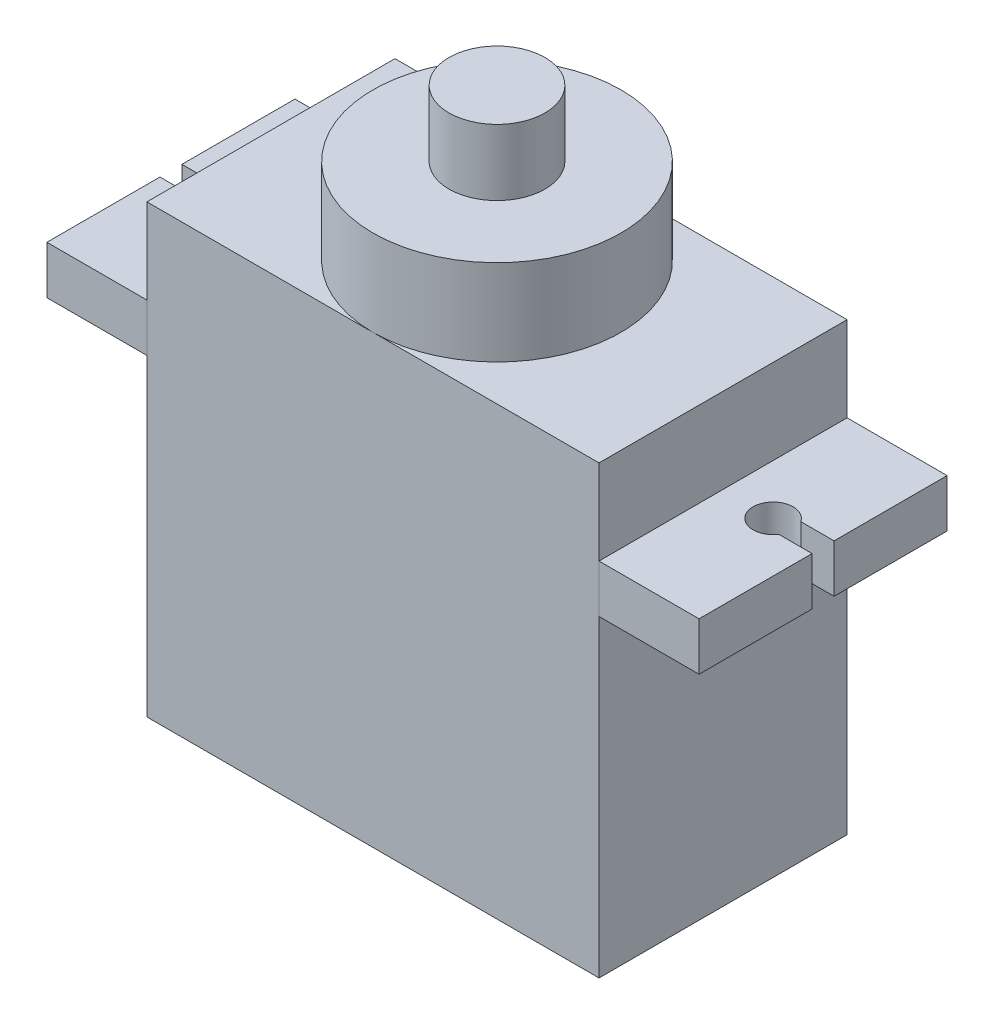
SolidWorks part; units mm, degrees
ref_plane "前视基准面" through (0, 0, 0) normal (0, 0, 1) x (1, 0, 0)
ref_plane "上视基准面" through (0, 0, 0) normal (0, 1, 0) x (1, 0, 0)
ref_plane "右视基准面" through (0, 0, 0) normal (1, 0, 0) x (0, 0, -1)
sketch "草图1" plane through (0, 0, 0) normal (0, 1, 0) x (1, 0, 0)
  line L1 (-11.3, 6.2) -> (11.3, 6.2)
  line L2 (-11.3, 6.2) -> (-11.3, -6.2)
  line L3 (-11.3, -6.2) -> (11.3, -6.2)
  line L4 (11.3, 6.2) -> (11.3, -6.2)
  line L5 (0, -6.2) -> (0, 6.2) construction
  line L6 (-11.3, 0) -> (11.3, 0) construction
  point P0 (0, 0)
  dimension "D1" = 22.6
  dimension "D2" = 12.4
extrude "凸台-拉伸1" add sketch "草图1" along normal blind 22.3
sketch "草图2" plane through (0, 0, 6.2) normal (0, 0, 1) x (1, 0, 0)
  line L0 (11.3, 22.3) -> (11.3, 0) construction
  line L1 (11.3, 18.05) -> (16.3, 18.05)
  line L2 (11.3, 18.05) -> (11.3, 15.65)
  line L3 (11.3, 15.65) -> (16.3, 15.65)
  line L4 (16.3, 18.05) -> (16.3, 15.65)
  line L5 (-11.3, 22.3) -> (11.3, 22.3) construction
  line L6 (0, 0) -> (0, 13.1092) construction
  line L7 (-11.3, 15.65) -> (-16.3, 15.65)
  line L8 (-16.3, 18.05) -> (-16.3, 15.65)
  line L9 (-11.3, 18.05) -> (-16.3, 18.05)
  line L10 (-11.3, 18.05) -> (-11.3, 15.65)
  dimension "D1" = 4.25
  dimension "D2" = 2.4
  dimension "D3" = 5
extrude "凸台-拉伸2" add sketch "草图2" against normal through all separate body
sketch "草图3" plane through (0, 18.05, 0) normal (0, 1, 0) x (1, 0, 0)
  line L0 (14.6352, 0.55) -> (16.3, 0.55)
  line L1 (16.3, 6.2) -> (16.3, -6.2) construction
  line L2 (16.3, 0.55) -> (16.3, -0.55)
  line L3 (16.3, -0.55) -> (14.6352, -0.55)
  line L4 (0, 0) -> (13.8, 0) construction
  line L5 (0, 0) -> (0, 7.8737) construction
  line L12 (-14.6352, -0.55) -> (-16.3, -0.55)
  line L13 (-16.3, 0.55) -> (-14.6352, 0.55)
  line L19 (-16.3, 0.55) -> (-16.3, -0.55)
  arc A0 (14.6352, 0.55) -> (14.6352, -0.55) centre (13.8, 0) ccw
  arc A1 (-14.6352, 0.55) -> (-14.6352, -0.55) centre (-13.8, 0) cw
  dimension "D1" = 2
  dimension "D2" = 2.5
  dimension "D3" = 1.1
extrude "切除-拉伸1" cut sketch "草图3" against normal through all
sketch "草图4" plane through (0, 22.3, 0) normal (0, 1, 0) x (1, 0, 0)
  circle A0 centre (0, 0) radius 6.2
  dimension "D1" = 12.4
extrude "凸台-拉伸3" add sketch "草图4" along normal blind 4.3
sketch "草图5" plane through (0, 26.6, 0) normal (0, 1, 0) x (1, 0, 0)
  circle A0 centre (0, 0) radius 2.4
  dimension "D1" = 4.8
extrude "凸台-拉伸4" add sketch "草图5" along normal blind 3.3
